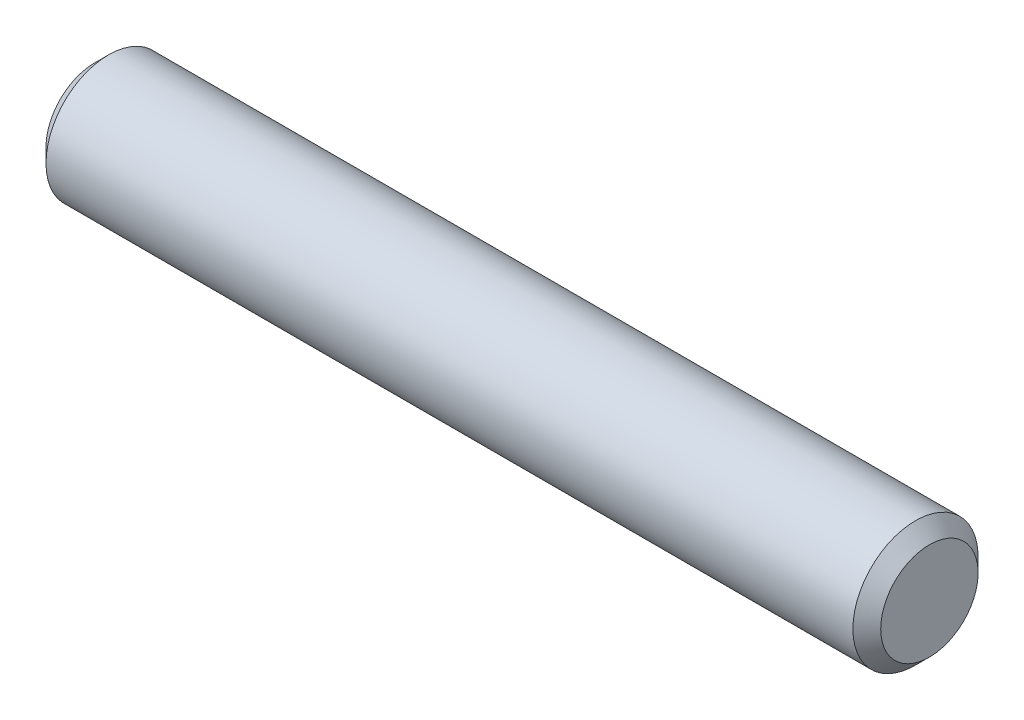
SolidWorks part; units mm, degrees
ref_plane "前视基准面" through (0, 0, 0) normal (0, 0, 1) x (1, 0, 0)
ref_plane "上视基准面" through (0, 0, 0) normal (0, 1, 0) x (1, 0, 0)
ref_plane "右视基准面" through (0, 0, 0) normal (1, 0, 0) x (0, 0, -1)
sketch "草图1" plane through (0, 0, 0) normal (0, 0, 1) x (1, 0, 0)
  line L0 (-6.3202, 0) -> (6.9944, 0) construction
  line L1 (-5.3427, 0) -> (-5.3427, 0.9)
  line L2 (-5.3427, 0.9) -> (6.6573, 0.9)
  line L3 (6.6573, 0.9) -> (6.6573, 0)
  line L4 (-5.3427, 0) -> (6.6573, 0)
  dimension "D1" = 12
  dimension "D2" = 0.9
revolve "旋转1" add sketch "草图1" angle 360 about L0
chamfer "倒角1" distance 0.2 angle 45 2 edges at (-5.3427, 0, 0.9) (6.6573, 0, 0.9)
